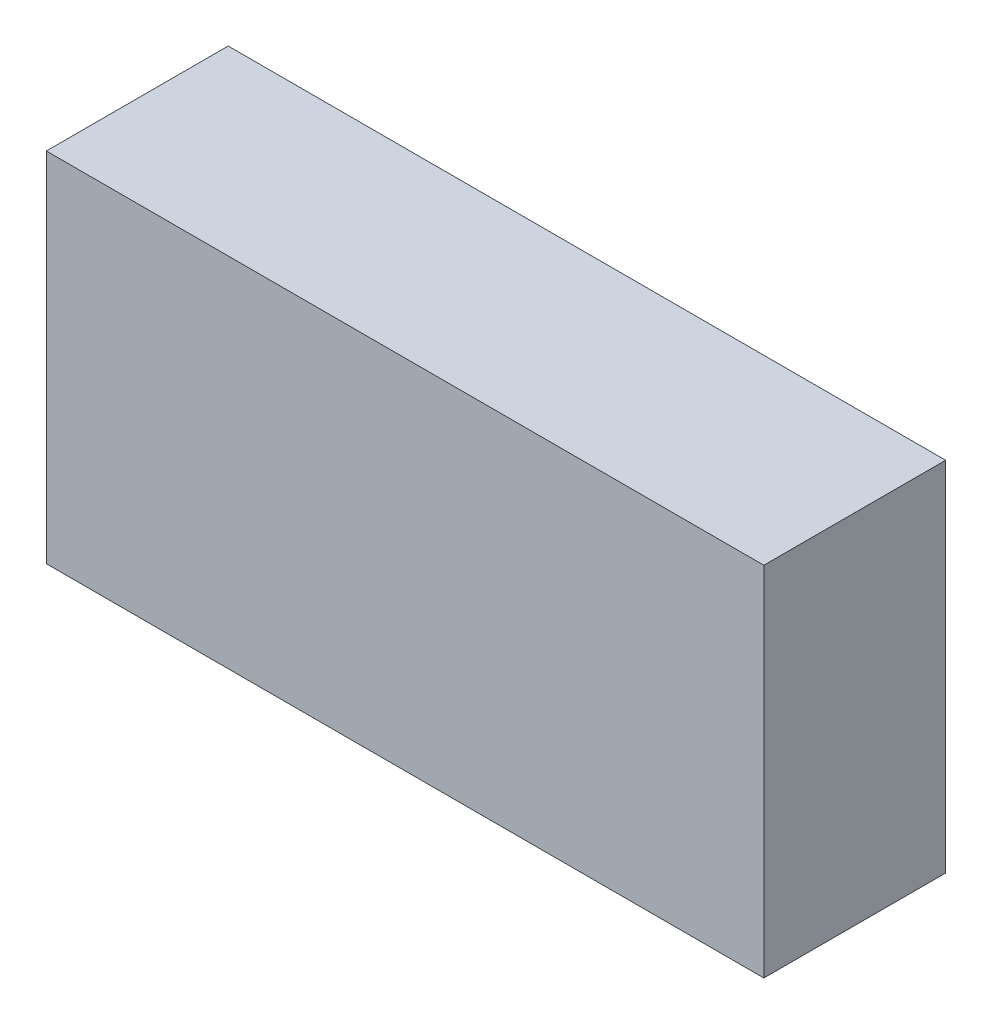
SolidWorks part; units mm, degrees
ref_plane "Front Plane" through (0, 0, 0) normal (0, 0, 1) x (1, 0, 0)
ref_plane "Top Plane" through (0, 0, 0) normal (0, 1, 0) x (1, 0, 0)
ref_plane "Right Plane" through (0, 0, 0) normal (1, 0, 0) x (0, 0, -1)
sketch "Sketch1" plane through (0, 0, 0) normal (0, 0, 1) x (1, 0, 0)
  line L0 (-1.973, 0.983) -> (1.973, 0.983)
  line L1 (1.973, 0.983) -> (1.973, -0.983)
  line L2 (1.973, -0.983) -> (-1.973, -0.983)
  line L3 (-1.973, -0.983) -> (-1.973, 0.983)
extrude "Component_Outline" add sketch "Sketch1" along normal blind 1 separate body
sketch3d "3DSketch1"
  line L0 (0, 0, 0) -> (1, 0, 0)
  line L1 (0, 0, 0) -> (0, 1, 0)
  line L2 (0, 0, 0) -> (0, 0, 1)
  point P0 (0, 0, 0)
